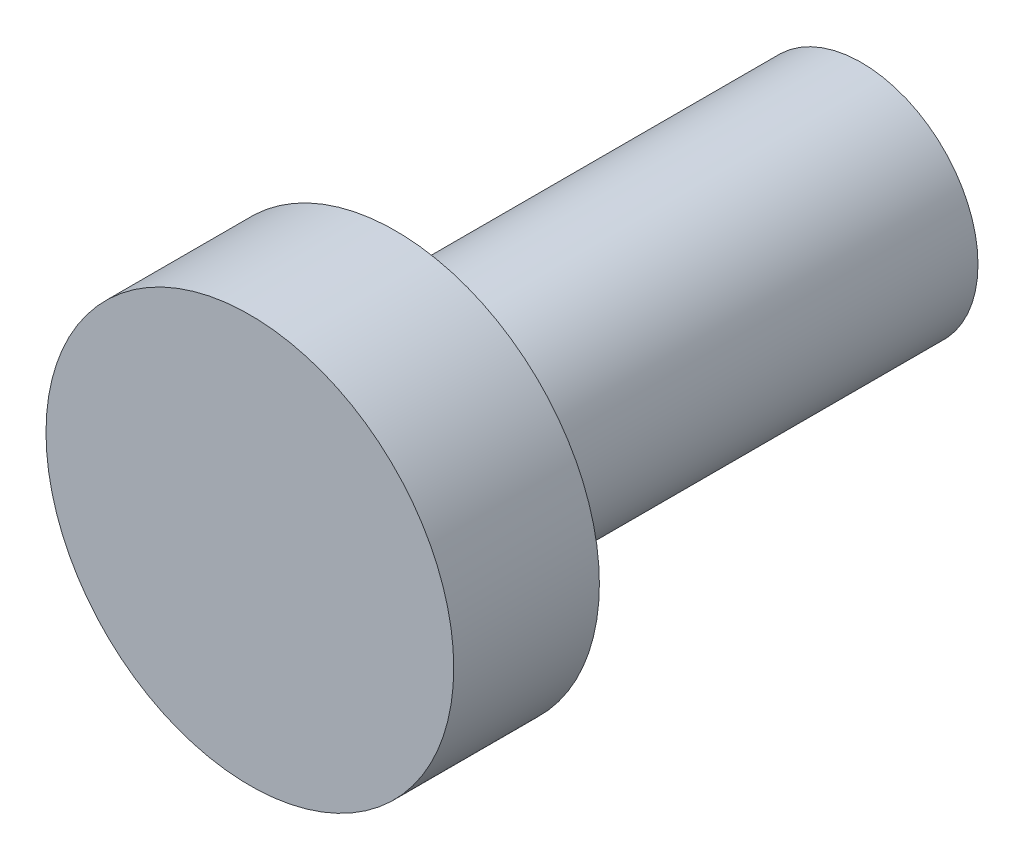
SolidWorks part; units mm, degrees
ref_plane "Front Plane" through (0, 0, 0) normal (0, 0, 1) x (1, 0, 0)
ref_plane "Top Plane" through (0, 0, 0) normal (0, 1, 0) x (1, 0, 0)
ref_plane "Right Plane" through (0, 0, 0) normal (1, 0, 0) x (0, 0, -1)
sketch "Sketch1" plane through (0, 0, 0) normal (0, 0, 1) x (1, 0, 0)
  circle A0 centre (0, 0) radius 2
extrude "Boss-Extrude1" add sketch "Sketch1" against normal blind 8
sketch "Sketch2" plane through (0, 0, 0) normal (0, 0, 1) x (1, 0, 0)
  circle A0 centre (0, 0) radius 3.5
extrude "Boss-Extrude2" add sketch "Sketch2" along normal blind 2.5
